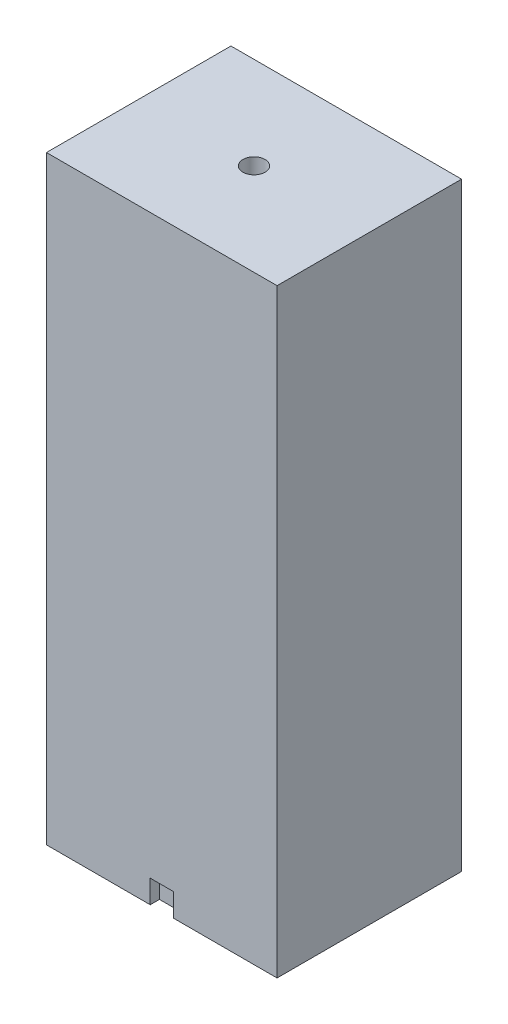
SolidWorks part; units mm, degrees
ref_plane "Front Plane" through (0, 0, 0) normal (0, 0, 1) x (1, 0, 0)
ref_plane "Top Plane" through (0, 0, 0) normal (0, 1, 0) x (1, 0, 0)
ref_plane "Right Plane" through (0, 0, 0) normal (1, 0, 0) x (0, 0, -1)
sketch "Sketch1" plane through (0, 0, 0) normal (0, 0, 1) x (1, 0, 0)
  line L1 (0, 0) -> (63.5, 0)
  line L2 (0, 0) -> (0, 165.1)
  line L3 (0, 165.1) -> (63.5, 165.1)
  line L4 (63.5, 0) -> (63.5, 165.1)
  dimension "D1" = 63.5
  dimension "D2" = 165.1
extrude "Boss-Extrude1" add sketch "Sketch1" along normal blind 50.8
sketch "Sketch2" plane through (0, 0, 0) normal (0, -1, 0) x (1, 0, 0)
  line L0 (31.75, 50.8) -> (31.75, 39.2313) construction
  line L1 (0, 50.8) -> (63.5, 50.8) construction
  line L2 (0, 25.4) -> (-6.5254, 25.4) construction
  line L3 (0, 50.8) -> (0, 0) construction
  circle A0 centre (31.75, 25.4) radius 3.048
  dimension "D1" = 6.096
extrude "Boss-Extrude2" add sketch "Sketch2" along normal blind 5.08
sketch "Sketch3" plane through (0, 165.1, 0) normal (0, 1, 0) x (1, 0, 0)
  circle A0 centre (31.75, -25.4) radius 3.048
extrude "Cut-Extrude1" cut sketch "Sketch3" against normal blind 6.35
ref_plane "Plane1" through (31.75, 0, 0) normal (1, 0, 0) x (0, 0, -1)
ref_plane "Plane2" through (0, 0, 25.4) normal (0, 0, 1) x (1, 0, 0)
sketch "Sketch4" plane through (0, 0, 50.8) normal (0, 0, 1) x (1, 0, 0)
  line L0 (0, 0) -> (63.5, 0) construction
  line L1 (34.925, 0) -> (28.575, 0)
  line L2 (34.925, 0) -> (34.925, 6.35)
  line L3 (34.925, 6.35) -> (28.575, 6.35)
  line L4 (28.575, 0) -> (28.575, 6.35)
  line L6 (31.75, 165.1) -> (31.75, -25.4174) construction
  line L7 (63.5, 165.1) -> (0, 165.1) construction
  point P10 (35.2145, 6.35)
  dimension "D1" = 6.35
  dimension "D2" = 6.35
extrude "Cut-Extrude2" cut sketch "Sketch4" against normal blind 2.54
